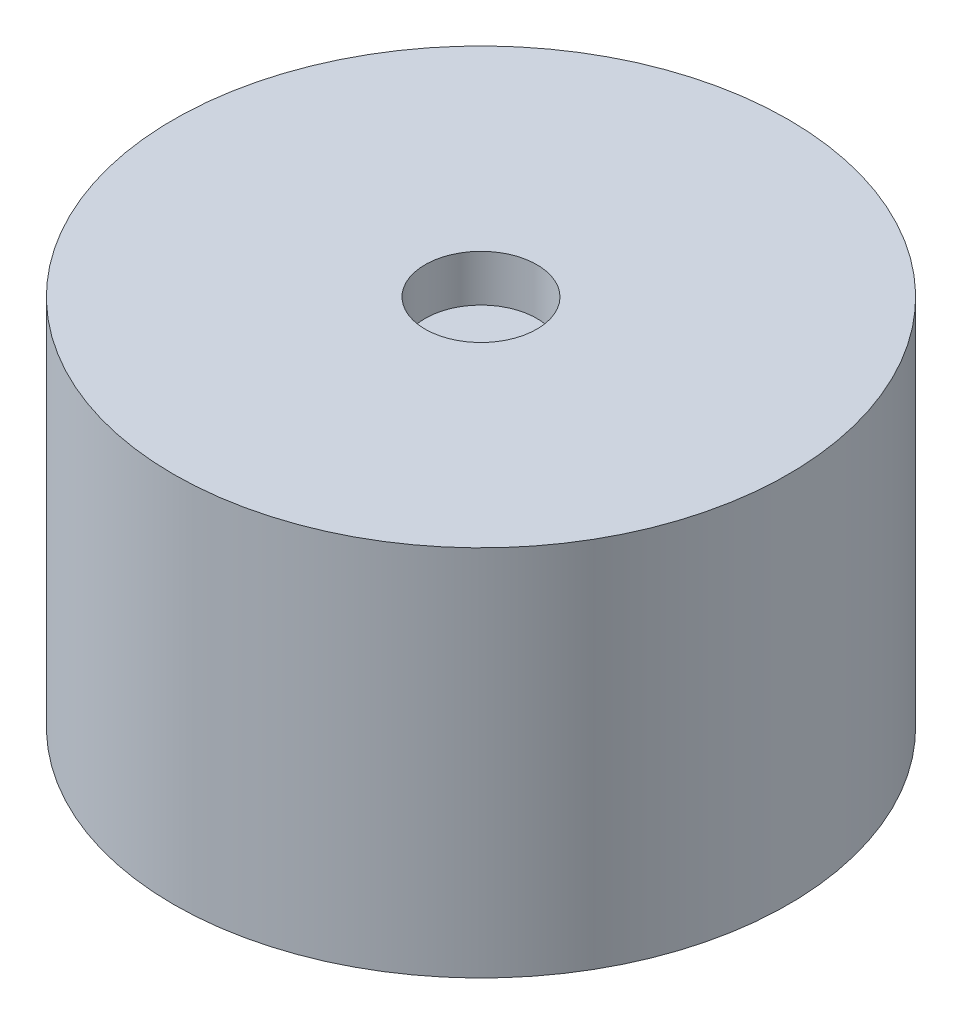
SolidWorks part; units mm, degrees
ref_plane "前视基准面" through (0, 0, 0) normal (0, 0, 1) x (1, 0, 0)
ref_plane "上视基准面" through (0, 0, 0) normal (0, 1, 0) x (1, 0, 0)
ref_plane "右视基准面" through (0, 0, 0) normal (1, 0, 0) x (0, 0, -1)
sketch "草图1" plane through (0, 0, 0) normal (0, 1, 0) x (1, 0, 0)
  circle A0 centre (0, 0) radius 33
extrude "凸台-拉伸1" add sketch "草图1" along normal blind 40
sketch "草图2" plane through (0, 40, 0) normal (0, 1, 0) x (1, 0, 0)
  circle A0 centre (0, 0) radius 6
extrude "切除-拉伸1" cut sketch "草图2" against normal blind 5
